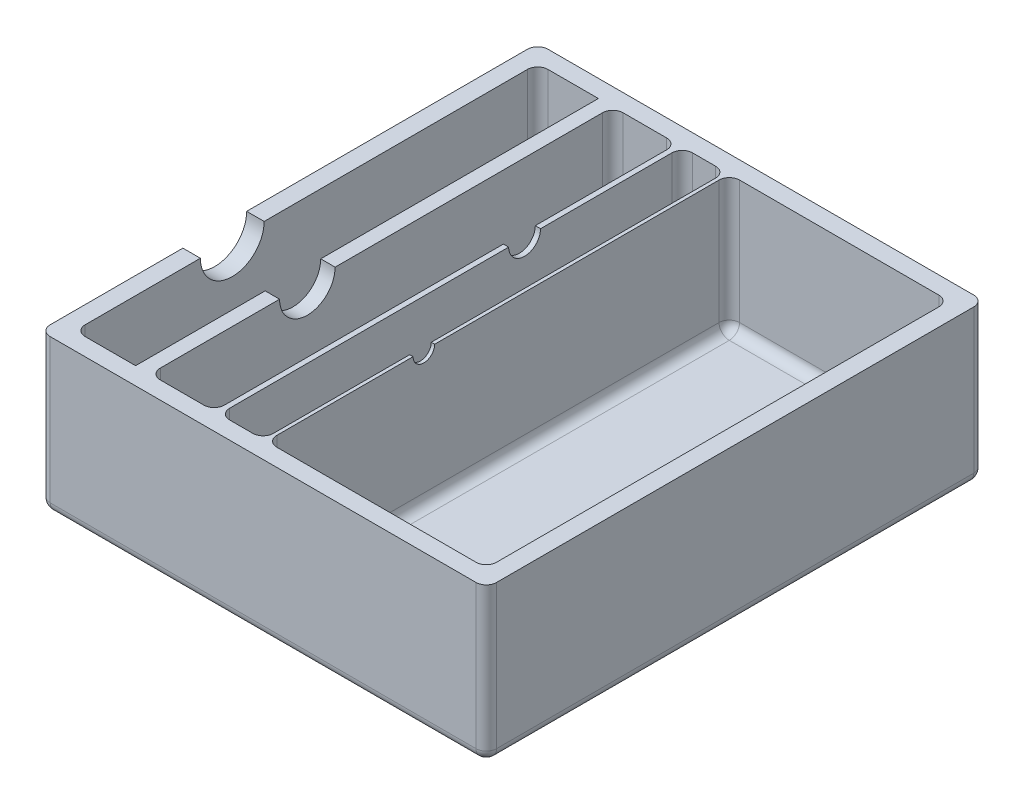
SolidWorks part; units mm, degrees
material "ABS PC"
ref_plane "Front Plane" through (0, 0, 0) normal (0, 0, 1) x (1, 0, 0)
ref_plane "Top Plane" through (0, 0, 0) normal (0, 1, 0) x (1, 0, 0)
ref_plane "Right Plane" through (0, 0, 0) normal (1, 0, 0) x (0, 0, -1)
sketch "Sketch2" plane through (0, 0, 0) normal (0, 1, 0) x (1, 0, 0)
  line L1 (-2000, -2250) -> (2000, -2250)
  line L2 (-2000, -2250) -> (-2000, 2250)
  line L3 (-2000, 2250) -> (2000, 2250)
  line L4 (2000, -2250) -> (2000, 2250)
  line L5 (-2000, -2250) -> (2000, 2250) construction
  line L6 (-2000, 2250) -> (2000, -2250) construction
  point P1 (0, 0)
  dimension "D1" = 4500
  dimension "D2" = 4000
extrude "Boss-Extrude1" add sketch "Sketch2" along normal blind 200
sketch "Sketch5" plane through (0, 0, 0) normal (0, 1, 0) x (1, 0, 0)
  line L10 (2000, 2250) -> (-2000, 2250) construction
  line L11 (2000, -2250) -> (2000, 2250) construction
  line L12 (-2000, -2250) -> (2000, -2250) construction
  line L13 (-2000, 2250) -> (-2000, -2250) construction
  line L14 (-2170, -2420) -> (2170, -2420)
  line L15 (2170, -2420) -> (2170, 2420)
  line L16 (2170, 2420) -> (-2170, 2420)
  line L17 (-2170, 2420) -> (-2170, -2420)
  line L18 (-2170, -2420) -> (2170, -2420)
  line L19 (2170, -2420) -> (2170, 2420)
  line L20 (2170, 2420) -> (-2170, 2420)
  line L21 (-2170, 2420) -> (-2170, -2420)
  line L22 (2000, 2250) -> (-2000, 2250)
  line L23 (2000, -2250) -> (2000, 2250)
  line L24 (-2000, -2250) -> (2000, -2250)
  line L25 (-2000, 2250) -> (-2000, -2250)
  dimension "D1" = 170
extrude "Boss-Extrude2" add sketch "Sketch5" along normal blind 1500
sketch "Sketch6" plane through (0, 200, 0) normal (0, 1, 0) x (1, 0, 0)
  line L0 (-1410, 2250) -> (-1270, 2250)
  line L1 (-1410, 2250) -> (-1410, -2250)
  line L2 (-1270, 2250) -> (-1270, -2250)
  line L3 (-1410, -2250) -> (-1270, -2250)
  line L4 (2000, 2250) -> (-2000, 2250) construction
  line L6 (-2000, 2250) -> (-2000, -2250) construction
  line L7 (-2000, -2250) -> (2000, -2250) construction
  line L8 (-646, -2250) -> (-595, -2250)
  line L9 (-646, -2250) -> (-646, 2250)
  line L10 (-595, -2250) -> (-595, 2250)
  line L11 (-646, 2250) -> (-595, 2250)
  line L12 (-170, 2250) -> (-137, 2250)
  line L13 (-170, 2250) -> (-170, -2250)
  line L14 (-137, 2250) -> (-137, -2250)
  line L15 (-170, -2250) -> (-137, -2250)
  line L16 (2000, 2250) -> (-2000, 2250) construction
  line L17 (-2000, -2250) -> (2000, -2250) construction
  point P10 (-620.5, 2250)
  dimension "D1" = 140
  dimension "D2" = 590
  dimension "D3" = 624
  dimension "D4" = 51
  dimension "D5" = 425
  dimension "D6" = 33
extrude "Boss-Extrude4" add sketch "Sketch6" along normal up to surface (1300 mm away) up to face at (0, 1500, 0)
sketch "Sketch7" plane through (-2170, 0, 0) normal (-1, 0, 0) x (0, 0, 1)
  line L0 (-2420, 1500) -> (2420, 1500) construction
  line L1 (2420, 1500) -> (2420, 0) construction
  circle A0 centre (720, 1500) radius 310
  dimension "D1" = 620
  dimension "D2" = 1700
extrude "Cut-Extrude1" cut sketch "Sketch7" against normal up to next
sketch "Sketch8" plane through (-1410, 0, 0) normal (-1, 0, 0) x (0, 0, 1)
  line L0 (-2250, 1500) -> (2250, 1500) construction
  line L1 (2420, 1500) -> (2420, 0) construction
  circle A0 centre (720, 1500) radius 270
  dimension "D1" = 540
  dimension "D2" = 1700
extrude "Cut-Extrude2" cut sketch "Sketch8" against normal up to next
sketch "Sketch9" plane through (-170, 0, 0) normal (-1, 0, 0) x (0, 0, 1)
  line L0 (-2250, 1500) -> (2250, 1500) construction
  line L1 (2420, 1500) -> (2420, 0) construction
  circle A0 centre (720, 1500) radius 105
  dimension "D1" = 210
  dimension "D2" = 1700
extrude "Cut-Extrude3" cut sketch "Sketch9" against normal up to next
sketch "Sketch10" plane through (-646, 0, 0) normal (-1, 0, 0) x (0, 0, 1)
  line L0 (-2250, 1500) -> (2250, 1500) construction
  circle A0 centre (-717.5, 1500) radius 155
  dimension "D1" = 310
  dimension "D2" = 1167.5
extrude "Cut-Extrude4" cut sketch "Sketch10" against normal up to next
fillet "Fillet1" radius 100 38 edges at (-958, 200, 2250) (-1270, 200, 0) (-958, 200, -2250) (-646, 200, 0) (-1705, 200, 2250) (-2000, 200, 0) (-1705, 200, -2250) (-1410, 200, 0) (931.5, 200, -2250) (2000, 200, 0) (931.5, 200, 2250) (-137, 200, 0) (-382.5, 200, 2250) (-595, 200, 0) (-382.5, 200, -2250) (-170, 200, 0) (2000, 850, -2250) (2000, 850, 2250) (-170, 850, -2250) (-595, 850, -2250) (-137, 850, -2250) (-137, 850, 2250) (-170, 850, 2250) (-595, 850, 2250) (-646, 850, 2250) (-1270, 850, 2250) (-646, 850, -2250) (-1270, 850, -2250) (-2000, 850, -2250) (-2000, 850, 2250) (0, 0, -2420) (2170, 750, -2420) (2170, 0, 0) (2170, 750, 2420) (0, 0, 2420) (-2170, 0, 0) (-2170, 750, -2420) (-2170, 750, 2420)
